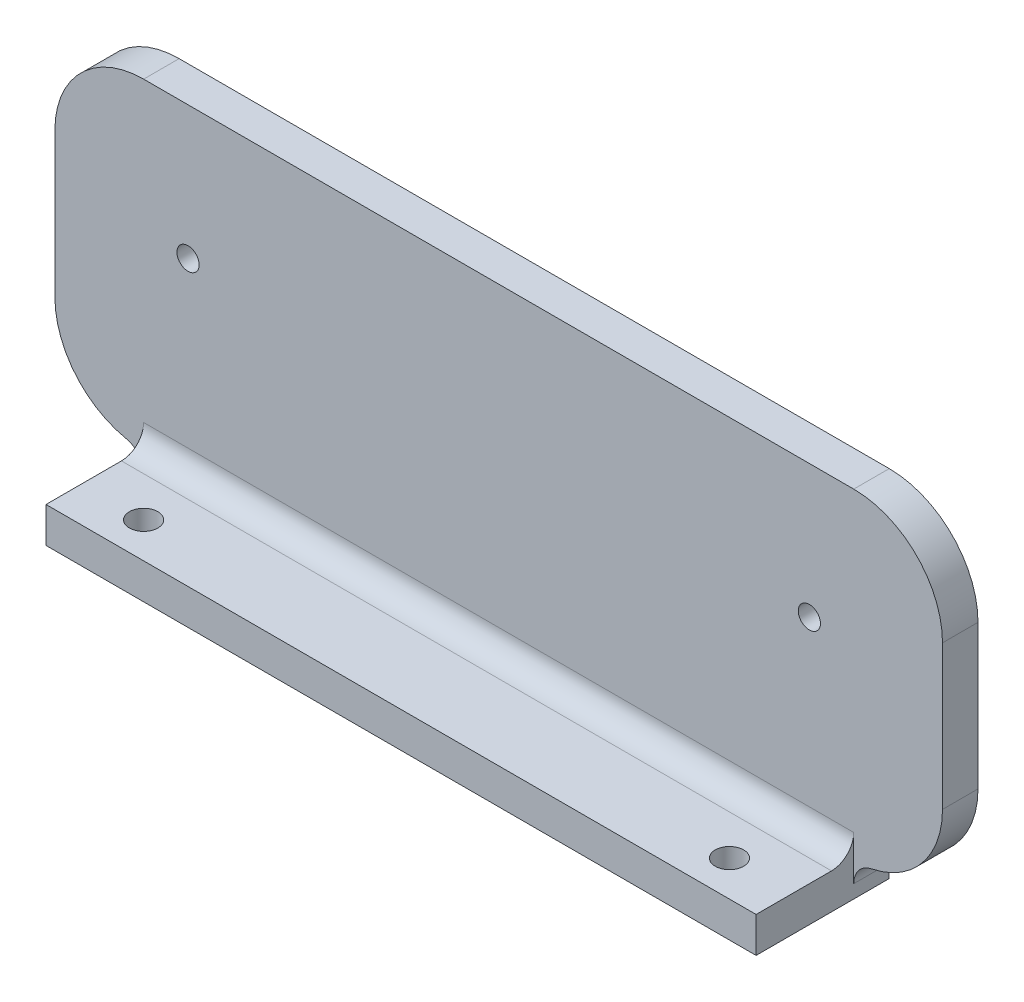
SolidWorks part; units mm, degrees
material "Du"
ref_plane "Front Plane" through (0, 0, 0) normal (0, 0, 1) x (1, 0, 0)
ref_plane "Top Plane" through (0, 0, 0) normal (0, 1, 0) x (1, 0, 0)
ref_plane "Right Plane" through (0, 0, 0) normal (1, 0, 0) x (0, 0, -1)
sketch "Sketch1" plane through (0, 0, 0) normal (0, 0, 1) x (1, 0, 0)
  line L1 (-50, 18) -> (50, 18)
  line L2 (-50, 18) -> (-50, -18)
  line L3 (-50, -18) -> (50, -18)
  line L4 (50, 18) -> (50, -18)
  line L5 (-50, 18) -> (50, -18) construction
  line L6 (-50, -18) -> (50, 18) construction
  point P0 (0, 0)
  dimension "D1" = 100
  dimension "D2" = 36
extrude "Boss-Extrude1" add sketch "Sketch1" along normal blind 4
sketch "Sketch5" plane through (0, -18, 0) normal (0, -1, 0) x (1, 0, 0)
  line L1 (-40, 15) -> (40, 15)
  line L2 (-40, 15) -> (-40, 0)
  line L3 (-40, 0) -> (40, 0)
  line L4 (40, 15) -> (40, 0)
  line L5 (-40, 15) -> (40, 0) construction
  line L6 (-40, 0) -> (40, 15) construction
  point P0 (0, 7.5)
  dimension "D1" = 15
  dimension "D2" = 80
extrude "Boss-Extrude3" add sketch "Sketch5" along normal blind 4
sketch "Sketch6" plane through (0, 0, 4) normal (0, 0, 1) x (1, 0, 0)
  line L0 (-50, 18) -> (-50, -18) construction
  line L1 (50, 18) -> (-50, 18) construction
  line L2 (50, -18) -> (50, 18) construction
  circle A0 centre (35, 3) radius 1.25
  circle A1 centre (-35, 3) radius 1.25
  dimension "D1" = 2.5
  dimension "D2" = 2.5
  dimension "D3" = 15
  dimension "D4" = 15
  dimension "D5" = 15
  dimension "D6" = 15
extrude "Cut-Extrude3" cut sketch "Sketch6" against normal through all
fillet "Fillet3" radius 2.5 1 edges at (0, -18, 4)
fillet "Fillet4" radius 2.5 2 edges at (40, -18, 2) (-40, -18, 2)
fillet "Fillet5" radius 10 4 edges at (-50, -18, 2) (50, -18, 2) (-50, 18, 2) (50, 18, 2)
sketch "Sketch7" plane through (0, -22, 0) normal (0, -1, 0) x (1, 0, 0)
  line L0 (22, 0) -> (-22, 0) construction
  circle A1 centre (33, 11) radius 1.6
  circle A3 centre (-33, 11) radius 1.6
  dimension "D1" = 3.2
  dimension "D4" = 3.2
  dimension "D5" = 11
  dimension "D8" = 11
extrude "Cut-Extrude4" cut sketch "Sketch7" against normal blind 4
sketch "Sketch3" plane through (0, 0, 4) normal (0, 0, 1) x (1, 0, 0)
  line L0 (-50, 8) -> (-50, -8.2526) construction
  line L1 (40, 18) -> (-40, 18) construction
  line L2 (50, -8.2526) -> (50, 8) construction
  circle A0 centre (35, 3) radius 1.25
  circle A1 centre (-35, 3) radius 1.25
  dimension "D1" = 2.5
  dimension "D2" = 2.5
  dimension "D3" = 15
  dimension "D4" = 15
  dimension "D5" = 15
  dimension "D6" = 15
